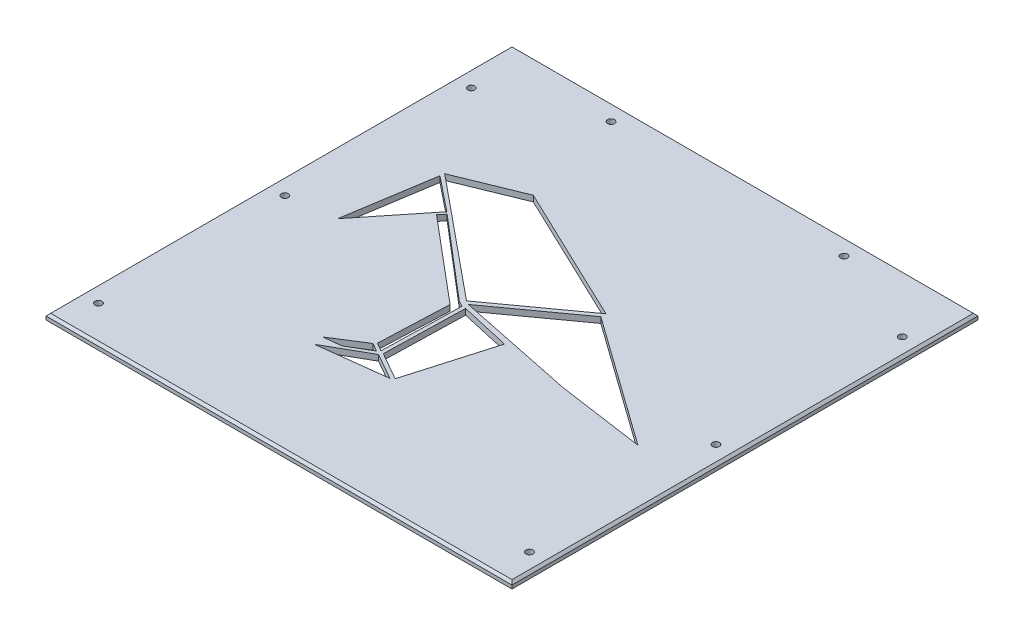
SolidWorks part; units mm, degrees
ref_plane "Alzado" through (0, 0, 0) normal (0, 0, 1) x (1, 0, 0)
ref_plane "Planta" through (0, 0, 0) normal (0, 1, 0) x (1, 0, 0)
ref_plane "Vista lateral" through (0, 0, 0) normal (1, 0, 0) x (0, 0, -1)
sketch "Croquis1" plane through (0, 0, 0) normal (0, 1, 0) x (1, 0, 0)
  line L1 (-188.3268, 170.428) -> (211.6732, 170.428)
  line L2 (-188.3268, 170.428) -> (-188.3268, -229.572)
  line L3 (-188.3268, -229.572) -> (211.6732, -229.572)
  line L4 (211.6732, 170.428) -> (211.6732, -229.572)
  circle A0 centre (-173.3268, 120.428) radius 3
  circle A1 centre (-173.3268, -199.572) radius 3
  circle A2 centre (196.6732, -199.572) radius 3
  circle A3 centre (196.6732, 120.428) radius 3
  circle A4 centre (-173.3268, -39.572) radius 3
  circle A5 centre (196.6732, -39.572) radius 3
  circle A6 centre (-88.3268, 155.428) radius 3
  circle A7 centre (111.6732, 155.428) radius 3
  dimension "D3" = 6
  dimension "D4" = 6
  dimension "D5" = 6
  dimension "D6" = 6
  dimension "D7" = 6
  dimension "D8" = 6
  dimension "D14" = 6
  dimension "D15" = 6
  dimension "D1" = 400
  dimension "D2" = 400
  dimension "D9" = 50
  dimension "D10" = 30
  dimension "D11" = 160
  dimension "D12" = 15
  dimension "D13" = 15
  dimension "D16" = 100
  dimension "D17" = 100
  dimension "D18" = 15
extrude "Saliente-Extruir1" add sketch "Croquis1" along normal blind 5
chamfer "Chaflán1" distance 2 angle 45 4 edges at (211.6732, 5, 29.572) (11.6732, 5, -170.428) (-188.3268, 5, 29.572) (11.6732, 5, 229.572)
sketch "Croquis2" plane through (0, 5, 0) normal (0, 1, 0) x (1, 0, 0)
  line L0 (20.5071, 1076.5625) -> (1897.4294, 1076.5625) construction
  line L1 (-91.7775, 17.9396) -> (-133.4864, -34.0971)
  line L2 (-133.4864, -34.0971) -> (-121.4993, 41.7625)
  line L3 (-120.9404, 45.2999) -> (-66.9663, 67.346)
  line L4 (-66.9663, 67.346) -> (52.3541, 10.3882)
  line L5 (52.3541, 10.3882) -> (-17.0915, -39.8577)
  line L7 (163.7752, -73.5934) -> (52.3541, 6.0091)
  line L8 (163.7752, -73.5934) -> (89.0909, -62.957)
  line L9 (89.0909, -62.957) -> (-13.6044, -41.7248)
  line L10 (31.3118, -55.6605) -> (10.1695, -128.3586)
  line L11 (7.6464, -130.3626) -> (-49.9893, -137.4021)
  line L12 (-49.9893, -137.4021) -> (-15.0038, -117.4529)
  line L13 (-13.5589, -114.8344) -> (-11.8352, -45.8821)
  line L14 (-94.0059, 11.3162) -> (-21.4212, -49.6543)
  line L15 (-21.4212, -49.6543) -> (-23.8688, -109.6196)
  line L16 (-25.5723, -111.6975) -> (-51.9316, -128.3586)
  line L17 (-51.9316, -128.3586) -> (-37.171, -126.8493)
  line L18 (-13.5589, -114.8344) -> (10.1695, -128.3586)
  line L19 (-15.0038, -117.4529) -> (7.6464, -130.3626)
  line L20 (-19.7954, -43.3156) -> (-15.0038, -45.8821)
  line L21 (-120.9404, 45.2999) -> (-17.0915, -39.8577)
  line L22 (52.3541, 6.0091) -> (-13.6044, -41.7248)
  line L23 (-121.4993, 41.7625) -> (-91.7775, 17.9396)
  line L24 (-89.8326, 16.2845) -> (-19.7954, -43.3156)
  line L25 (-89.8326, 16.2845) -> (-94.0059, 11.3162)
  line L26 (-11.8352, -45.8821) -> (31.3118, -55.6605)
  line L27 (-15.0038, -45.8821) -> (-16.6979, -113.6507)
  line L28 (-18.3235, -115.7724) -> (-37.171, -126.8493)
  line L29 (-25.5723, -111.6975) -> (-18.3235, -115.7724)
  line L30 (-23.8688, -109.6196) -> (-16.6979, -113.6507)
  point P2 (903.4376, 504.8568)
extrude "Cortar-Extruir1" cut sketch "Croquis2" against normal blind 10
